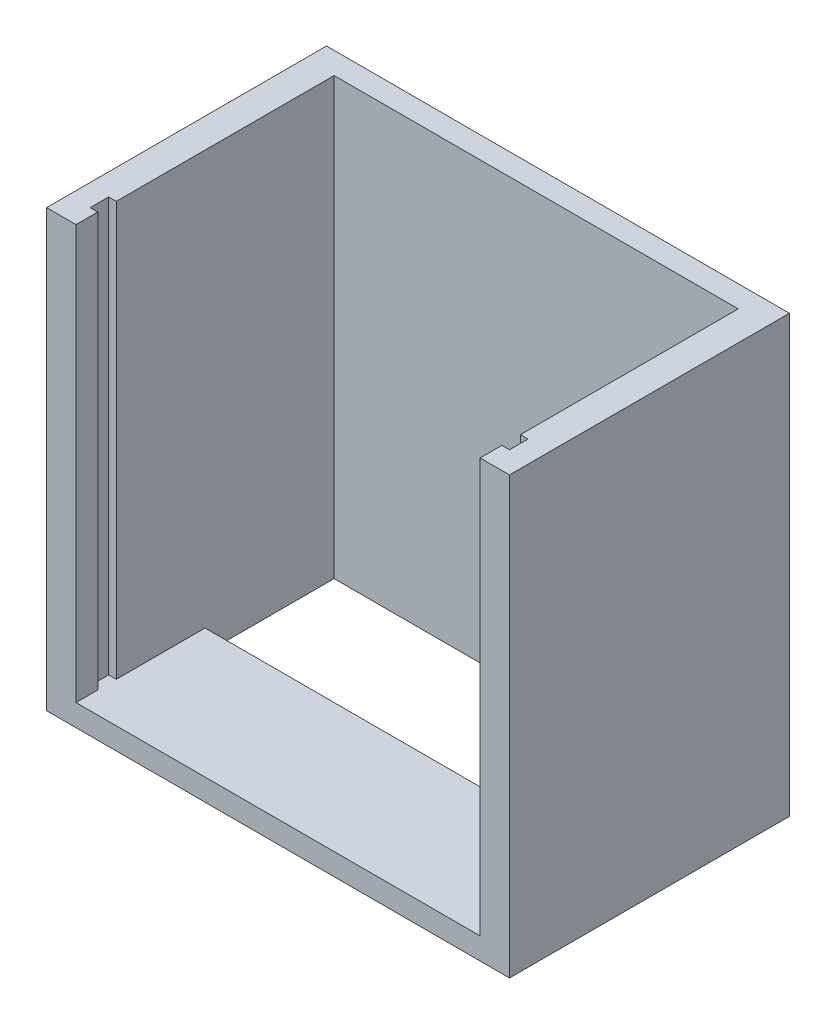
SolidWorks part; units mm, degrees
ref_plane "Front Plane" through (0, 0, 0) normal (0, 0, 1) x (1, 0, 0)
ref_plane "Top Plane" through (0, 0, 0) normal (0, 1, 0) x (1, 0, 0)
ref_plane "Right Plane" through (0, 0, 0) normal (1, 0, 0) x (0, 0, -1)
sketch "Sketch1" plane through (0, 0, 0) normal (0, 1, 0) x (1, 0, 0)
  line L5 (-62.899, -24.3935) -> (-24.399, -24.3935)
  line L6 (-62.899, -24.3935) -> (-62.899, -26.0935)
  line L7 (-62.899, -26.0935) -> (-24.399, -26.0935)
  line L8 (-24.399, -24.3935) -> (-24.399, -26.0935)
  line L9 (-62.199, -22.3935) -> (-25.099, -22.3935)
  line L10 (-62.199, -22.3935) -> (-62.199, -28.0935)
  line L11 (-62.199, -28.0935) -> (-25.099, -28.0935)
  line L12 (-25.099, -22.3935) -> (-25.099, -28.0935)
  line L13 (-64.899, -22.3935) -> (-22.399, -22.3935)
  line L14 (-64.899, -22.3935) -> (-64.899, -28.0935)
  line L15 (-64.899, -28.0935) -> (-22.399, -28.0935)
  line L16 (-22.399, -22.3935) -> (-22.399, -28.0935)
  point P8 (-24.399, -25.2435)
  dimension "D1" = 38.5
  dimension "D2" = 1.7
  dimension "D3" = 2
  dimension "D4" = 2
  dimension "D5" = 0.7
  dimension "D6" = 0.7
  dimension "D7" = 2
  dimension "D8" = 2
  dimension "D9" = 2
  dimension "D10" = 2
extrude "Boss-Extrude1" add sketch "Sketch1" along normal blind 38 contours L14 L15 L10 L7 L6 L5 L13 | L16 L13 L12 L5 L8 L7 L15
sketch "Sketch2" plane through (0, 0, 0) normal (0, 1, 0) x (1, 0, 0)
  line L1 (-64.899, -28.0935) -> (-22.399, -28.0935)
  line L2 (-64.899, -28.0935) -> (-64.899, -22.3935)
  line L3 (-64.899, -22.3935) -> (-22.399, -22.3935)
  line L4 (-22.399, -28.0935) -> (-22.399, -22.3935)
  dimension "D1" = 42.5
  dimension "D2" = 5.7
extrude "Boss-Extrude2" add sketch "Sketch2" against normal blind 2
sketch "Sketch3" plane through (0, 0, 22.3935) normal (0, 0, -1) x (-1, 0, 0)
  line L1 (22.399, 38) -> (64.899, 38)
  line L2 (22.399, 38) -> (22.399, -2)
  line L3 (22.399, -2) -> (64.899, -2)
  line L4 (64.899, 38) -> (64.899, -2)
  line L5 (25.099, 0) -> (62.199, 0)
  line L6 (25.099, 0) -> (25.099, 38)
  line L7 (25.099, 38) -> (62.199, 38)
  line L8 (62.199, 0) -> (62.199, 38)
  line M6 (62.199, 38) -> (62.199, 0)
  line M7 (62.199, 0) -> (25.099, 0)
  line M8 (25.099, 0) -> (25.099, 38)
  line M9 (25.099, 38) -> (22.399, 38)
  line M10 (22.399, 38) -> (22.399, -2)
  line M11 (22.399, -2) -> (64.899, -2)
  line M12 (64.899, -2) -> (64.899, 38)
  line M13 (64.899, 38) -> (62.199, 38)
  dimension "D1" = 42.5
  dimension "D2" = 40
  dimension "D3" = 38
  dimension "D4" = 37.1
extrude "Boss-Extrude3" add sketch "Sketch3" along normal blind 18 contours M13 M6 M7 M8 M9 M10 M11 M12
sketch "Sketch4" plane through (0, 0, 4.3935) normal (0, 0, -1) x (-1, 0, 0)
  line L1 (22.399, 38) -> (64.899, 38)
  line L2 (22.399, 38) -> (22.399, -2)
  line L3 (22.399, -2) -> (64.899, -2)
  line L4 (64.899, 38) -> (64.899, -2)
extrude "Boss-Extrude4" add sketch "Sketch4" along normal blind 2
sketch "Sketch5" plane through (0, 0, 0) normal (0, 1, 0) x (1, 0, 0)
  line L0 (-62.199, -16.2435) -> (-25.099, -16.2435)
  line L1 (-62.199, -4.3935) -> (-25.099, -4.3935)
  line L2 (-62.199, -4.3935) -> (-62.199, -28.0935)
  line L3 (-62.199, -28.0935) -> (-25.099, -28.0935)
  line L4 (-25.099, -4.3935) -> (-25.099, -28.0935)
  line M5 (-25.099, -24.3935) -> (-25.099, -4.3935)
  line M6 (-25.099, -4.3935) -> (-62.199, -4.3935)
  line M7 (-62.199, -4.3935) -> (-62.199, -24.3935)
  dimension "D1" = 37.1
  dimension "D2" = 23.7
  dimension "D3" = 11.85
extrude "Cut-Extrude1" cut sketch "Sketch5" against normal through all contours L0 M7 M5 M6
equation "\"camera side length\" = 38"
equation "\"camera module panel thickness\"= 1.7"
equation "\"tolerance\"= 0.5"
equation "\"D1@Sketch1\"=\"camera side length\"+\"tolerance\""
equation "\"D2@Sketch1\"=\"camera module panel thickness\""
equation "\"camera module side clearance\"= 0.7"
equation "\"camera mount thickness\" = 2"
equation "\"D3@Sketch1\"=\"camera mount thickness\""
equation "\"D4@Sketch1\"=\"camera mount thickness\""
equation "\"D5@Sketch1\"=\"camera module side clearance\""
equation "\"D6@Sketch1\"=\"camera module side clearance\""
equation "\"D7@Sketch1\"=\"camera mount thickness\""
equation "\"D8@Sketch1\"=\"camera mount thickness\""
equation "\"D9@Sketch1\"=\"camera mount thickness\""
equation "\"D10@Sketch1\"=\"camera mount thickness\""
equation "\"D1@Boss-Extrude1\"=\"camera side length\""
equation "\"D1@Boss-Extrude2\"=\"camera mount thickness\""
equation "\"camera module hole offset\"= 4.65"
equation "\"camera module hole diameter\"= 2.33"
equation "\"camera mount inner depth\"= 20"
equation "\"D1@Boss-Extrude3\"=\"camera mount inner depth\"-\"camera mount thickness\""
equation "\"D1@Boss-Extrude4\"=\"camera mount thickness\""
